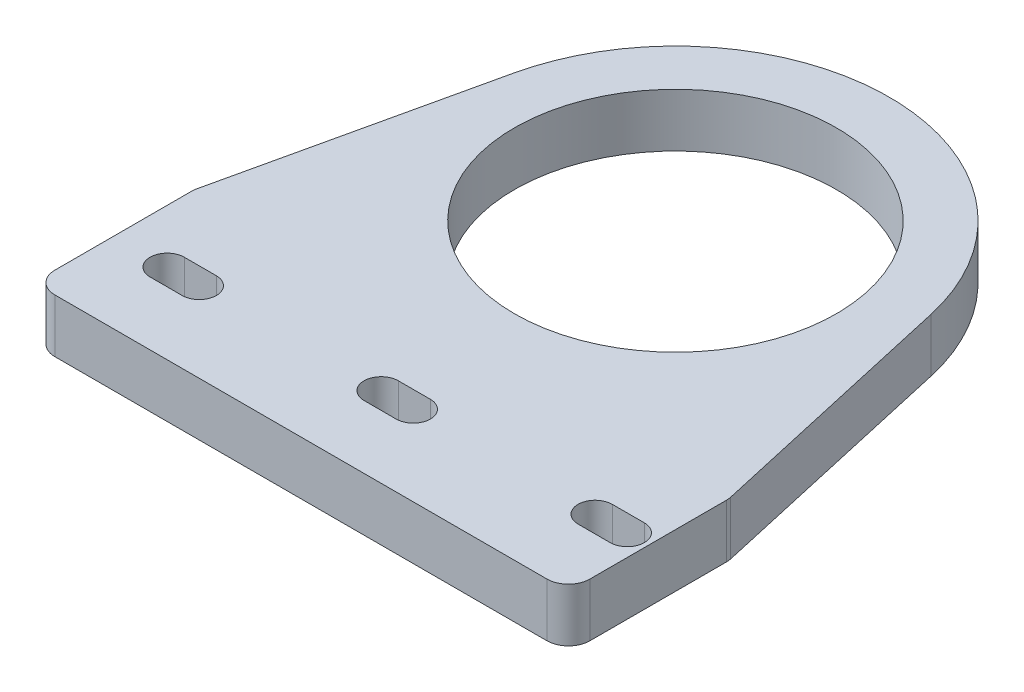
SolidWorks part; units mm, degrees
material "Thornel Mat VMA"
ref_plane "前视基准面" through (0, 0, 0) normal (0, 0, 1) x (1, 0, 0)
ref_plane "上视基准面" through (0, 0, 0) normal (0, 1, 0) x (1, 0, 0)
ref_plane "右视基准面" through (0, 0, 0) normal (1, 0, 0) x (0, 0, -1)
other "Configuration Table"
sketch "草图1" plane through (0, 0, 0) normal (0, 1, 0) x (1, 0, 0)
  circle A0 centre (0, 0) radius 6.5
  circle A1 centre (0, 0) radius 20
  circle A2 centre (0, 0) radius 9.5 construction
  circle A3 centre (0, 9.5) radius 1.6
  circle A4 centre (8.2272, -4.75) radius 1.6
  circle A5 centre (-8.2272, -4.75) radius 1.6
  point P14 (0, 0)
  dimension "D1" = 13
  dimension "30" = 40
  dimension "D3" = 19
  dimension "D4" = 3.2
  dimension "D5" = 3
extrude "凸台-拉伸1" add sketch "草图1" along normal blind 5
sketch "草图2" plane through (0, 5, 0) normal (0, 1, 0) x (1, 0, 0)
  line L0 (0, 0) -> (0, -20) construction
  line L1 (-25, -27.5) -> (25, -27.5) construction
  line L2 (-25, -20) -> (25, -20)
  line L3 (-25, -20) -> (-25, -35)
  line L4 (-25, -35) -> (25, -35)
  line L5 (25, -20) -> (25, -35)
  circle A0 centre (-20, -27.5) radius 1.6
  circle A1 centre (20, -27.5) radius 1.6
  circle A2 centre (0, -27.5) radius 1.6
  dimension "D4" = 3.2
  dimension "D5" = 3.2
  dimension "D6" = 3.2
  dimension "D1" = 20
  dimension "D2" = 50
  dimension "D3" = 15
  dimension "D7" = 5
  dimension "D8" = 5
extrude "凸台-拉伸2" add sketch "草图2" against normal blind 5 separate body
sketch "草图4" plane through (0, 5, 0) normal (0, 1, 0) x (1, 0, 0)
  line L0 (-25, -20) -> (-19.5122, 4.3902)
  line L1 (-25, -20) -> (25, -20)
  line L2 (25, -20) -> (19.5122, 4.3902)
  circle A0 centre (0, 0) radius 20 construction
  circle A1 centre (0, 0) radius 20
  line M8 (25, -20) -> (-25, -20)
extrude "凸台-拉伸4" add sketch "草图4" against normal blind 5 contours A1 L0 L1 | A1 L2 M8
sketch "草图5" plane through (0, 5, 0) normal (0, 1, 0) x (1, 0, 0)
  circle A0 centre (-8.2272, -4.75) radius 3.5
  circle A1 centre (8.2272, -4.75) radius 3.5
  circle A2 centre (0, 9.5) radius 3.5
  dimension "D1" = 7
  dimension "D2" = 7
  dimension "D3" = 7
extrude "切除-拉伸1" cut sketch "草图5" against normal blind 3
fillet "圆角1" radius 2 4 edges at (-25, 2.5, 20) (-25, 2.5, 35) (25, 2.5, 20) (25, 2.5, 35)
sketch "草图6" plane through (0, 5, 0) normal (0, 1, 0) x (1, 0, 0)
  circle A0 centre (0, 0) radius 15.05
  dimension "D1" = 30.1
extrude "切除-拉伸2" cut sketch "草图6" against normal through all
sketch "草图7" plane through (0, 5, 0) normal (0, 1, 0) x (1, 0, 0)
  line L0 (-20, -27.5) -> (-17, -27.5) construction
  line L1 (-20, -25.9) -> (-17, -25.9)
  line L2 (-20, -29.1) -> (-17, -29.1)
  line L3 (0, -27.5) -> (3, -27.5) construction
  line L4 (20, -27.5) -> (23, -27.5) construction
  line L5 (0, -25.9) -> (3, -25.9)
  line L6 (0, -29.1) -> (3, -29.1)
  line L8 (20, -25.9) -> (23, -25.9)
  line L9 (20, -29.1) -> (23, -29.1)
  arc A0 (-20, -25.9) -> (-20, -29.1) centre (-20, -27.5) ccw
  arc A1 (-17, -29.1) -> (-17, -25.9) centre (-17, -27.5) ccw
  arc A2 (0, -25.9) -> (0, -29.1) centre (0, -27.5) ccw
  arc A3 (3, -29.1) -> (3, -25.9) centre (3, -27.5) ccw
  arc A4 (20, -25.9) -> (20, -29.1) centre (20, -27.5) ccw
  arc A5 (23, -29.1) -> (23, -25.9) centre (23, -27.5) ccw
  point P3 (-18.5, -27.5)
  point P13 (1.5, -27.5)
  point P21 (21.5, -27.5)
  dimension "D2" = 1.6
  dimension "D4" = 1.6
  dimension "D6" = 1.6
  dimension "D1" = 3
  dimension "D3" = 3
  dimension "D5" = 3
extrude "切除-拉伸3" cut sketch "草图7" against normal through all
